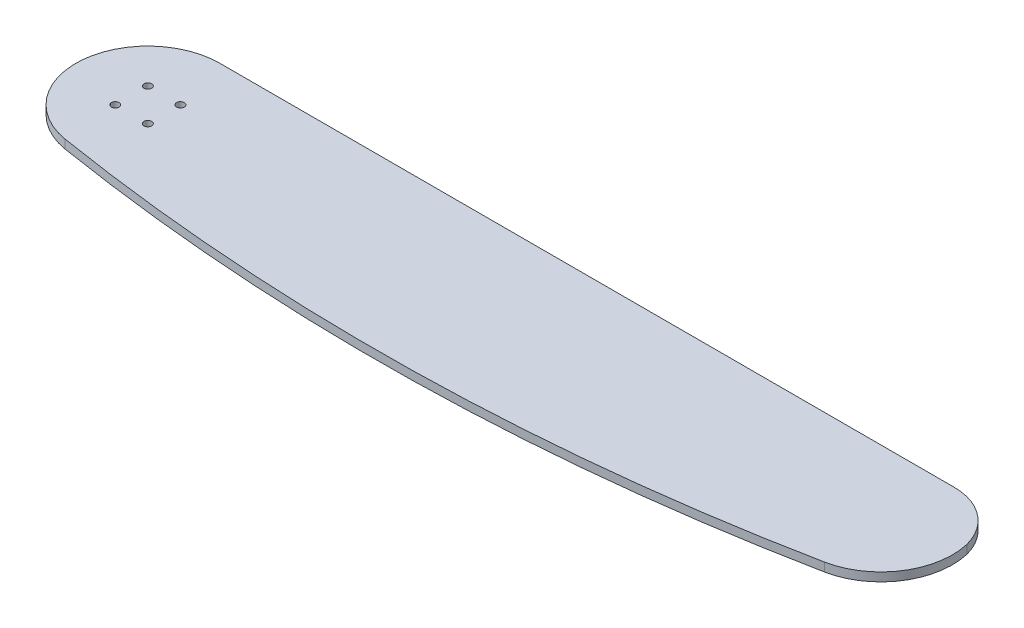
SolidWorks part; units mm, degrees
ref_plane "Front Plane" through (0, 0, 0) normal (0, 0, 1) x (1, 0, 0)
ref_plane "Top Plane" through (0, 0, 0) normal (0, 1, 0) x (1, 0, 0)
ref_plane "Right Plane" through (0, 0, 0) normal (1, 0, 0) x (0, 0, -1)
sketch "Sketch1" plane through (0, 0, 0) normal (0, 1, 0) x (1, 0, 0)
  line L0 (19.3431, 30.6569) -> (30.6569, 30.6569) construction
  line L1 (0, 0) -> (300, 0) construction
  line L2 (0, 0) -> (0, 50) construction
  line L3 (0, 50) -> (300, 50) construction
  line L4 (300, 0) -> (300, 50) construction
  line L5 (30.6569, 30.6569) -> (30.6569, 19.3431) construction
  line L6 (30.6569, 19.3431) -> (19.3431, 19.3431) construction
  line L7 (19.3431, 19.3431) -> (19.3431, 30.6569) construction
  line L12 (25, 50) -> (280, 50)
  line L13 (0, 45) -> (300, 45) construction
  line L14 (0, 45) -> (0, 5) construction
  line L15 (0, 5) -> (300, 5) construction
  line L16 (300, 45) -> (300, 5) construction
  circle A0 centre (25, 25) radius 17.25 construction
  circle A1 centre (25, 25) radius 25
  circle A2 centre (25, 25) radius 8 construction
  circle A3 centre (19.3431, 30.6569) radius 1.35
  circle A4 centre (30.6569, 30.6569) radius 1.35
  circle A5 centre (30.6569, 19.3431) radius 1.35
  arc A6 (280, 50) -> (299.3568, 35) centre (280, 30.0105) cw
  circle A7 centre (19.3431, 19.3431) radius 1.35
  arc A10 (299.3568, 35) -> (280, 5) centre (275.1386, 29.3815) cw
  arc A11 (21, 0.3221) -> (280, 5) centre (137.5546, 719.4033) ccw
  dimension "D3" = 34.5
  dimension "D4" = 16
  dimension "D5" = 2.7
  dimension "D8" = 20
  dimension "D9" = 40
  dimension "D10" = 255
  dimension "D6" = 5
  dimension "D1" = 50
  dimension "D2" = 300
  dimension "D7" = 10
  dimension "D11" = 21
extrude "Boss-Extrude1" add sketch "Sketch1" along normal blind 3
